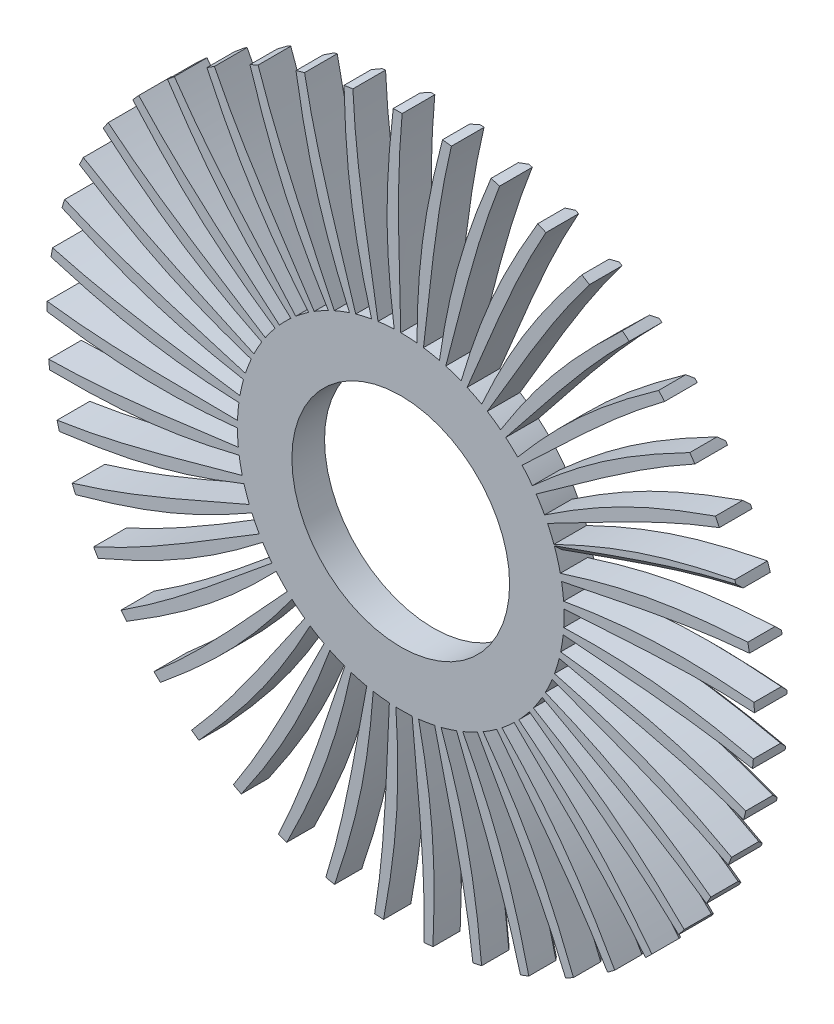
SolidWorks part; units mm, degrees
ref_plane "Front Plane" through (0, 0, 0) normal (0, 0, 1) x (1, 0, 0)
ref_plane "Top Plane" through (0, 0, 0) normal (0, 1, 0) x (1, 0, 0)
ref_plane "Right Plane" through (0, 0, 0) normal (1, 0, 0) x (0, 0, -1)
sketch "Sketch2" plane through (0, 0, 0) normal (0, 0, 1) x (1, 0, 0)
  arc A0 (255.3051, -201.1078) -> (260.3042, -194.5937) centre (0, 0) ccw
  arc A1 (-6, 149.88) -> (-20.876, 148.5402) centre (0, 0) ccw
  arc A2 (280.8092, -163.619) -> (284.8532, -156.4726) centre (0, 0) ccw
  arc A3 (315.0307, -79.8792) -> (316.9481, -71.8949) centre (0, 0) ccw
  arc A4 (323.0818, -35.258) -> (323.8695, -27.0846) centre (0, 0) ccw
  arc A5 (324.8446, 10.0494) -> (324.487, 18.2529) centre (0, 0) ccw
  arc A6 (300.8478, -122.9456) -> (303.8578, -115.3059) centre (0, 0) ccw
  arc A7 (224.8316, -234.6822) -> (230.6888, -228.9273) centre (0, 0) ccw
  arc A8 (66.3054, -318.1644) -> (74.3222, -316.3877) centre (0, 0) ccw
  arc A9 (109.9401, -305.8401) -> (117.6316, -302.965) centre (0, 0) ccw
  arc A10 (151.4349, -287.563) -> (158.6514, -283.6454) centre (0, 0) ccw
  arc A11 (21.3802, -324.296) -> (29.5663, -323.6523) centre (0, 0) ccw
  arc A12 (-23.9611, -324.1155) -> (-15.7652, -324.6174) centre (0, 0) ccw
  arc A13 (-68.8361, -317.6265) -> (-60.7898, -319.2642) centre (0, 0) ccw
  arc A14 (-112.3712, -304.9552) -> (-104.6312, -307.6968) centre (0, 0) ccw
  arc A15 (-153.7192, -286.3484) -> (-146.436, -290.1405) centre (0, 0) ccw
  arc A16 (-192.0752, -262.1681) -> (-185.3906, -266.9369) centre (0, 0) ccw
  arc A17 (-226.6927, -232.885) -> (-220.7369, -238.5377) centre (0, 0) ccw
  arc A18 (-256.8979, -199.069) -> (-251.7867, -205.4956) centre (0, 0) ccw
  arc A19 (-282.1028, -161.3784) -> (-277.9358, -168.4538) centre (0, 0) ccw
  arc A20 (-301.817, -120.5468) -> (-298.6752, -128.1333) centre (0, 0) ccw
  arc A21 (-315.6566, -77.3688) -> (-313.6012, -85.3187) centre (0, 0) ccw
  arc A22 (-323.3523, -32.685) -> (-322.4233, -40.8435) centre (0, 0) ccw
  arc A23 (-324.7543, 12.6351) -> (-324.9699, 4.4266) centre (0, 0) ccw
  arc A24 (-319.8354, 57.7092) -> (-321.1912, 49.6106) centre (0, 0) ccw
  arc A25 (-308.6912, 101.66) -> (-311.1609, 93.8289) centre (0, 0) ccw
  arc A26 (-291.5387, 143.6322) -> (-295.0743, 136.221) centre (0, 0) ccw
  arc A27 (-268.7117, 182.8087) -> (-273.2443, 175.9618) centre (0, 0) ccw
  arc A28 (-131.0066, 297.4261) -> (-138.4788, 294.0215) centre (0, 0) ccw
  arc A29 (-207.9134, 249.794) -> (-214.1577, 244.4616) centre (0, 0) ccw
  arc A30 (-171.1254, 276.2989) -> (-178.051, 271.8875) centre (0, 0) ccw
  arc A31 (-88.3379, 312.7641) -> (-96.2113, 310.4326) centre (0, 0) ccw
  arc A32 (-240.6546, 218.4271) -> (-246.096, 212.2776) centre (0, 0) ccw
  arc A33 (-43.9499, 322.0146) -> (-52.0711, 320.8015) centre (0, 0) ccw
  arc A34 (46.5119, 321.6545) -> (38.3709, 322.7269) centre (0, 0) ccw
  arc A35 (90.8249, 312.051) -> (82.9124, 314.246) centre (0, 0) ccw
  arc A36 (133.3701, 296.3738) -> (125.8401, 299.6486) centre (0, 0) ccw
  arc A37 (173.3194, 274.9279) -> (166.3185, 279.2189) centre (0, 0) ccw
  arc A38 (209.8953, 248.131) -> (203.5596, 253.3545) centre (0, 0) ccw
  arc A39 (242.3857, 216.5044) -> (236.8387, 222.5588) centre (0, 0) ccw
  arc A40 (270.1584, 180.6638) -> (265.508, 187.4313) centre (0, 0) ccw
  arc A41 (292.6728, 141.3068) -> (289.0095, 148.6557) centre (0, 0) ccw
  arc A42 (309.4907, 99.1994) -> (306.8858, 106.9866) centre (0, 0) ccw
  arc A43 (320.2846, 55.1613) -> (318.7888, 63.2352) centre (0, 0) ccw
  arc A44 (1.2936, 324.9974) -> (-6.9174, 324.9264) centre (0, 0) ccw
  arc A46 (-26.8009, 147.5863) -> (-41.3456, 144.1893) centre (0, 0) ccw
  arc A47 (-47.0801, 142.42) -> (-61.0105, 137.0318) centre (0, 0) ccw
  arc A48 (35.5449, 145.7277) -> (20.876, 148.5402) centre (0, 0) ccw
  arc A49 (14.9176, 149.2564) -> (0, 150) centre (0, 0) ccw
  arc A50 (-66.4429, 134.4817) -> (-79.4879, 127.2072) centre (0, 0) ccw
  arc A51 (-84.5126, 123.9259) -> (-96.4181, 114.9067) centre (0, 0) ccw
  arc A52 (-100.9372, 110.958) -> (-111.4717, 100.3696) centre (0, 0) ccw
  arc A53 (55.4804, 139.3626) -> (41.3456, 144.1893) centre (0, 0) ccw
  arc A54 (74.336, 130.2849) -> (61.0105, 137.0318) centre (0, 0) ccw
  arc A55 (91.7447, 118.6714) -> (79.4879, 127.2072) centre (0, 0) ccw
  arc A56 (-115.3973, 95.8304) -> (-124.3556, 83.8789) centre (0, 0) ccw
  arc A57 (-127.6113, 78.8376) -> (-134.8191, 65.7557) centre (0, 0) ccw
  arc A58 (107.3677, 104.7481) -> (96.4181, 114.9067) centre (0, 0) ccw
  arc A59 (120.901, 88.786) -> (111.4717, 100.3696) centre (0, 0) ccw
  arc A60 (132.081, 71.0958) -> (124.3556, 83.8789) centre (0, 0) ccw
  arc A61 (-137.3414, 60.3103) -> (-142.6585, 46.3525) centre (0, 0) ccw
  arc A62 (140.6902, 52.0218) -> (134.8191, 65.7557) centre (0, 0) ccw
  arc A63 (146.561, 31.9352) -> (142.6585, 46.3525) centre (0, 0) ccw
  arc A64 (-144.3984, 40.6091) -> (-147.7212, 26.0472) centre (0, 0) ccw
  arc A65 (-148.6448, 20.1175) -> (-149.9086, 5.2349) centre (0, 0) ccw
  arc A66 (-149.998, -0.7656) -> (-149.1783, -15.6793) centre (0, 0) ccw
  arc A67 (-148.4317, -21.6339) -> (-145.5444, -36.2883) centre (0, 0) ccw
  arc A68 (-143.9763, -42.081) -> (-139.0776, -56.191) centre (0, 0) ccw
  arc A69 (-136.7186, -61.7091) -> (-129.9038, -75) centre (0, 0) ccw
  arc A70 (-126.7998, -80.1361) -> (-118.2016, -92.3492) centre (0, 0) ccw
  arc A71 (-114.413, -97.0034) -> (-104.1988, -107.901) centre (0, 0) ccw
  arc A72 (-99.7993, -111.9826) -> (-88.1678, -121.3525) centre (0, 0) ccw
  arc A73 (-83.2431, -124.7821) -> (-70.4207, -132.4421) centre (0, 0) ccw
  arc A74 (-65.0667, -135.153) -> (-51.303, -140.9539) centre (0, 0) ccw
  arc A75 (-45.6238, -142.8932) -> (-31.1868, -146.7221) centre (0, 0) ccw
  arc A76 (-25.2929, -147.8522) -> (-10.4635, -149.6346) centre (0, 0) ccw
  arc A77 (-4.4697, -149.9334) -> (10.4635, -149.6346) centre (0, 0) ccw
  arc A78 (16.4405, -149.0963) -> (31.1868, -146.7221) centre (0, 0) ccw
  arc A79 (37.0307, -145.3572) -> (51.303, -140.9539) centre (0, 0) ccw
  arc A80 (56.9001, -138.789) -> (70.4207, -132.4421) centre (0, 0) ccw
  arc A81 (75.6621, -129.5193) -> (88.1678, -121.3525) centre (0, 0) ccw
  arc A82 (108.4314, -103.6467) -> (118.2016, -92.3492) centre (0, 0) ccw
  arc A83 (121.801, -87.5472) -> (129.9038, -75) centre (0, 0) ccw
  arc A84 (132.7998, -69.7438) -> (139.0776, -56.191) centre (0, 0) ccw
  arc A85 (141.2139, -50.5829) -> (145.5444, -36.2883) centre (0, 0) ccw
  arc A86 (146.8794, -30.4375) -> (149.1783, -15.6793) centre (0, 0) ccw
  arc A87 (92.9513, -117.7287) -> (104.1988, -107.901) centre (0, 0) ccw
  arc A88 (149.6861, -9.6996) -> (149.9086, 5.2349) centre (0, 0) ccw
  arc A89 (149.5793, 11.2271) -> (147.7212, 26.0472) centre (0, 0) ccw
  arc A90 (189.9822, -263.6888) -> (196.5832, -258.805) centre (0, 0) ccw
  spline S0 degree 3 poles (-6, 149.88) (-14.2223, 209.3858) (-13.9707, 256.8737) (-8.1395, 314.3894) (-7.1988, 322.5645) (-6.9174, 324.9264) knots 0 0 0 0 0.599001 0.668692 0.696915 0.696915 0.696915 0.696915
  spline S1 degree 3 poles (0, 150) (-1.2357, 209.7616) (-4.4377, 264.7336) (1.2936, 324.9974) knots 0 0 0 0 0.71612 0.71612 0.71612 0.71612
  spline S2 degree 3 poles (14.9176, 149.2564) (15.0569, 209.3274) (21.9152, 256.3182) (35.6943, 312.4626) (37.7635, 320.4272) (38.3709, 322.7269) knots 0 0 0 0 0.599001 0.668692 0.696915 0.696915 0.696915 0.696915
  spline S3 degree 3 poles (20.876, 148.5402) (27.9695, 207.8922) (32.4492, 262.7748) (46.5119, 321.6545) knots 0 0 0 0 0.71612 0.71612 0.71612 0.71612
  spline S4 degree 3 poles (35.5449, 145.7277) (44.0431, 205.1947) (57.3745, 250.7737) (78.8333, 304.4541) (81.9909, 312.0532) (82.9124, 314.246) knots 0 0 0 0 0.599001 0.668692 0.696915 0.696915 0.696915 0.696915
  spline S5 degree 3 poles (41.3456, 144.1893) (56.6303, 201.9765) (68.7046, 255.7014) (90.8249, 312.051) knots 0 0 0 0 0.71612 0.71612 0.71612 0.71612
  spline S6 degree 3 poles (55.4804, 139.3626) (72.1721, 197.0682) (91.7171, 240.3482) (120.4379, 290.5197) (124.6224, 297.6054) (125.8401, 299.6486) knots 0 0 0 0 0.599001 0.668692 0.696915 0.696915 0.696915 0.696915
  spline S7 degree 3 poles (61.0105, 137.0318) (84.1888, 192.1294) (103.6228, 243.6511) (133.3701, 296.3738) knots 0 0 0 0 0.71612 0.71612 0.71612 0.71612
  spline S8 degree 3 poles (74.336, 130.2849) (98.8963, 185.1059) (124.2745, 225.2446) (159.6984, 270.9306) (164.8282, 277.365) (166.3185, 279.2189) knots 0 0 0 0 0.599001 0.668692 0.696915 0.696915 0.696915 0.696915
  spline S9 degree 3 poles (79.4879, 127.2072) (110.1088, 178.5428) (136.524, 226.8584) (173.3194, 274.9279) knots 0 0 0 0 0.71612 0.71612 0.71612 0.71612
  spline S10 degree 3 poles (91.7447, 118.6714) (123.6956, 169.5408) (154.413, 205.7569) (195.8505, 246.0682) (201.8259, 251.7261) (203.5596, 253.3545) knots 0 0 0 0 0.599001 0.668692 0.696915 0.696915 0.696915 0.696915
  spline S11 degree 3 poles (96.4181, 114.9067) (133.8856, 161.4811) (166.768, 205.6502) (209.8953, 248.131) knots 0 0 0 0 0.71612 0.71612 0.71612 0.71612
  spline S12 degree 3 poles (107.3677, 104.7481) (146.0874, 150.6757) (181.5461, 182.2643) (228.1905, 216.4164) (234.8952, 221.1876) (236.8387, 222.5588) knots 0 0 0 0 0.599001 0.668692 0.696915 0.696915 0.696915 0.696915
  spline S13 degree 3 poles (111.4717, 100.3696) (155.0564, 141.2763) (193.766, 180.4392) (242.3857, 216.5044) knots 0 0 0 0 0.71612 0.71612 0.71612 0.71612
  spline S14 degree 3 poles (120.901, 88.786) (165.6356, 128.8779) (205.1456, 155.2242) (256.0891, 182.5523) (263.3926, 186.3439) (265.508, 187.4313) knots 0 0 0 0 0.599001 0.668692 0.696915 0.696915 0.696915 0.696915
  spline S15 degree 3 poles (124.3556, 83.8789) (173.2093, 118.3217) (216.9925, 151.7162) (270.1584, 180.6638) knots 0 0 0 0 0.71612 0.71612 0.71612 0.71612
  spline S16 degree 3 poles (132.081, 71.0958) (181.96, 104.5716) (224.7522, 125.1628) (279.0033, 145.135) (286.7633, 147.8732) (289.0095, 148.6557) knots 0 0 0 0 0.599001 0.668692 0.696915 0.696915 0.696915 0.696915
  spline S17 degree 3 poles (134.8191, 65.7557) (187.9908, 93.0641) (235.9956, 120.0402) (292.6728, 141.3068) knots 0 0 0 0 0.71612 0.71612 0.71612 0.71612
  spline S18 degree 3 poles (140.6902, 52.0218) (194.7428, 78.23) (239.9842, 92.6653) (296.4869, 104.8928) (304.5525, 106.5244) (306.8858, 106.9866) knots 0 0 0 0 0.599001 0.668692 0.696915 0.696915 0.696915 0.696915
  spline S19 degree 3 poles (142.6585, 46.3525) (199.1133, 65.9952) (250.4052, 86.0277) (309.4907, 99.1994) knots 0 0 0 0 0.71612 0.71612 0.71612 0.71612
  spline S20 degree 3 poles (146.561, 31.9352) (203.7351, 50.3657) (250.5452, 58.3641) (308.1998, 62.609) (316.414, 63.1022) (318.7888, 63.2352) knots 0 0 0 0 0.599001 0.668692 0.696915 0.696915 0.696915 0.696915
  spline S21 degree 3 poles (147.7212, 26.0472) (206.3603, 37.6417) (259.9411, 50.3408) (320.2846, 55.1613) knots 0 0 0 0 0.71612 0.71612 0.71612 0.71612
  spline S22 degree 3 poles (149.5793, 11.2271) (208.7619, 21.5211) (256.2296, 22.927) (313.9139, 19.1065) (322.1168, 18.4518) (324.487, 18.2529) knots 0 0 0 0 0.599001 0.668692 0.696915 0.696915 0.696915 0.696915
  spline S23 degree 3 poles (149.9086, 5.2349) (209.5907, 8.5556) (264.4174, 13.6741) (324.8446, 10.0494) knots 0 0 0 0 0.71612 0.71612 0.71612 0.71612
  spline S24 degree 3 poles (149.6861, -9.6996) (209.7254, -7.7423) (256.9268, -12.9564) (313.518, -24.7678) (321.55, -26.5578) (323.8695, -27.0846) knots 0 0 0 0 0.599001 0.668692 0.696915 0.696915 0.696915 0.696915
  spline S25 degree 3 poles (149.1783, -15.6793) (208.7417, -20.6971) (263.7472, -23.2588) (323.0818, -35.258) knots 0 0 0 0 0.71612 0.71612 0.71612 0.71612
  spline S26 degree 3 poles (146.8794, -30.4375) (206.6068, -36.8551) (252.6233, -48.5876) (307.0199, -68.16) (314.7245, -71.0504) (316.9481, -71.8949) knots 0 0 0 0 0.599001 0.668692 0.696915 0.696915 0.696915 0.696915
  spline S27 degree 3 poles (145.5444, -36.2883) (203.8298, -49.5469) (257.9434, -59.7389) (315.0307, -79.8792) knots 0 0 0 0 0.71612 0.71612 0.71612 0.71612
  spline S28 degree 3 poles (141.2139, -50.5829) (199.4669, -65.2506) (243.4027, -83.2732) (294.5459, -110.2256) (301.7734, -114.1602) (303.8578, -115.3059) knots 0 0 0 0 0.599001 0.668692 0.696915 0.696915 0.696915 0.696915
  spline S29 degree 3 poles (139.0776, -56.191) (194.9505, -77.4323) (247.1191, -95.0563) (300.8478, -122.9456) knots 0 0 0 0 0.71612 0.71612 0.71612 0.71612
  spline S30 degree 3 poles (132.7998, -69.7438) (188.4446, -92.376) (229.4445, -116.3378) (276.339, -150.1457) (282.9485, -155.0479) (284.8532, -156.4726) knots 0 0 0 0 0.599001 0.668692 0.696915 0.696915 0.696915 0.696915
  spline S31 degree 3 poles (129.9038, -75) (182.2768, -103.8106) (231.4849, -128.5236) (280.8092, -163.619) knots 0 0 0 0 0.71612 0.71612 0.71612 0.71612
  spline S32 degree 3 poles (121.801, -87.5472) (173.7544, -117.7034) (211.0205, -147.1382) (252.7534, -187.1435) (258.6164, -192.9178) (260.3042, -194.5937) knots 0 0 0 0 0.599001 0.668692 0.696915 0.696915 0.696915 0.696915
  spline S33 degree 3 poles (118.2016, -92.3492) (166.0552, -128.1684) (211.345, -159.4893) (255.3051, -201.1078) knots 0 0 0 0 0.71612 0.71612 0.71612 0.71612
  spline S34 degree 3 poles (108.4314, -103.6467) (155.6823, -140.7399) (188.4891, -175.0746) (224.2483, -220.4987) (229.2506, -227.0328) (230.6888, -228.9273) knots 0 0 0 0 0.599001 0.668692 0.696915 0.696915 0.696915 0.696915
  spline S35 degree 3 poles (104.1988, -107.901) (146.6016, -150.0315) (187.0916, -187.3507) (224.8316, -234.6822) knots 0 0 0 0 0.71612 0.71612 0.71612 0.71612
  spline S36 degree 3 poles (92.9513, -117.7287) (134.58, -161.037) (162.2891, -199.6034) (191.3784, -249.5622) (195.4226, -256.7288) (196.5832, -258.805) knots 0 0 0 0 0.599001 0.668692 0.696915 0.696915 0.696915 0.696915
  spline S37 degree 3 poles (88.1678, -121.3525) (124.2945, -168.9744) (159.1967, -211.5655) (189.9822, -263.6888) knots 0 0 0 0 0.71612 0.71612 0.71612 0.71612
  spline S38 degree 3 poles (75.6621, -129.5193) (110.8583, -178.1997) (132.9303, -220.2471) (154.7836, -273.7682) (157.7911, -281.4279) (158.6514, -283.6454) knots 0 0 0 0 0.599001 0.668692 0.696915 0.696915 0.696915 0.696915
  spline S39 degree 3 poles (70.4207, -132.4421) (99.5682, -184.6284) (128.2032, -231.6625) (151.4349, -287.563) knots 0 0 0 0 0.71612 0.71612 0.71612 0.71612
  spline S40 degree 3 poles (56.9001, -138.789) (84.9788, -191.8939) (100.9842, -236.604) (115.1761, -292.6456) (117.0882, -300.6494) (117.6316, -302.965) knots 0 0 0 0 0.599001 0.668692 0.696915 0.696915 0.696915 0.696915
  spline S41 degree 3 poles (51.303, -140.9539) (72.9039, -196.6888) (94.7143, -247.2504) (109.9401, -305.8401) knots 0 0 0 0 0.71612 0.71612 0.71612 0.71612
  spline S42 degree 3 poles (37.0307, -145.3572) (57.4453, -201.8532) (67.0725, -248.3557) (73.3268, -305.827) (74.1064, -314.019) (74.3222, -316.3877) knots 0 0 0 0 0.599001 0.668692 0.696915 0.696915 0.696915 0.696915
  spline S43 degree 3 poles (31.1868, -146.7221) (44.8206, -204.9209) (59.382, -258.0258) (66.3054, -318.1644) knots 0 0 0 0 0.71612 0.71612 0.71612 0.71612
  spline S44 degree 3 poles (16.4405, -149.0963) (28.7937, -207.8836) (31.8553, -255.2734) (30.0503, -313.0558) (29.6823, -321.2766) (29.5663, -323.6523) knots 0 0 0 0 0.599001 0.668692 0.696915 0.696915 0.696915 0.696915
  spline S45 degree 3 poles (10.4635, -149.6346) (15.865, -209.1645) (22.8938, -263.7791) (21.3802, -324.296) knots 0 0 0 0 0.71612 0.71612 0.71612 0.71612
  spline S46 degree 3 poles (-4.4697, -149.9334) (-0.4183, -209.8678) (-3.9819, -257.2225) (-13.8111, -314.1914) (-15.3197, -322.2809) (-15.7652, -324.6174) knots 0 0 0 0 0.599001 0.668692 0.696915 0.696915 0.696915 0.696915
  spline S47 degree 3 poles (-10.4635, -149.6346) (-13.3995, -209.3369) (-14.04, -264.3982) (-23.9611, -324.1155) knots 0 0 0 0 0.71612 0.71612 0.71612 0.71612
  spline S48 degree 3 poles (-25.2929, -147.8522) (-29.6222, -207.7672) (-39.7416, -254.1651) (-57.4037, -309.2116) (-60.0234, -317.0124) (-60.7898, -319.2642) knots 0 0 0 0 0.599001 0.668692 0.696915 0.696915 0.696915 0.696915
  spline S49 degree 3 poles (-31.1868, -146.7221) (-42.4032, -205.4348) (-50.7004, -259.8712) (-68.8361, -317.6265) knots 0 0 0 0 0.71612 0.71612 0.71612 0.71612
  spline S50 degree 3 poles (-45.6238, -142.8932) (-58.2495, -201.6226) (-74.7278, -246.1606) (-99.8789, -298.2133) (-103.5589, -305.5737) (-104.6312, -307.6968) knots 0 0 0 0 0.599001 0.668692 0.696915 0.696915 0.696915 0.696915
  spline S51 degree 3 poles (-51.303, -140.9539) (-70.5815, -197.5341) (-86.3741, -250.286) (-112.3712, -304.9552) knots 0 0 0 0 0.71612 0.71612 0.71612 0.71612
  spline S52 degree 3 poles (-65.0667, -135.153) (-85.7431, -191.5537) (-108.2595, -233.3649) (-140.4102, -281.4106) (-145.0787, -288.1872) (-146.436, -290.1405) knots 0 0 0 0 0.599001 0.668692 0.696915 0.696915 0.696915 0.696915
  spline S53 degree 3 poles (-70.4207, -132.4421) (-97.386, -185.7887) (-120.3666, -235.8293) (-153.7192, -286.3484) knots 0 0 0 0 0.71612 0.71612 0.71612 0.71612
  spline S54 degree 3 poles (-83.2431, -124.7821) (-111.5678, -177.7563) (-139.684, -216.027) (-178.2085, -259.1307) (-183.7747, -265.1915) (-185.3906, -266.9369) knots 0 0 0 0 0.599001 0.668692 0.696915 0.696915 0.696915 0.696915
  spline S55 degree 3 poles (-88.1678, -121.3525) (-122.2951, -170.4271) (-152.0163, -216.7824) (-192.0752, -262.1681) knots 0 0 0 0 0.71612 0.71612 0.71612 0.71612
  spline S56 degree 3 poles (-99.7993, -111.9826) (-135.2209, -160.4992) (-168.3898, -194.4843) (-212.5382, -231.807) (-218.8937, -237.0342) (-220.7369, -238.5377) knots 0 0 0 0 0.599001 0.668692 0.696915 0.696915 0.696915 0.696915
  spline S57 degree 3 poles (-104.1988, -107.901) (-144.8238, -151.7483) (-180.7071, -193.5161) (-226.6927, -232.885) knots 0 0 0 0 0.71612 0.71612 0.71612 0.71612
  spline S58 degree 3 poles (-114.413, -97.0034) (-156.2421, -140.1181) (-193.818, -169.1563) (-242.7311, -199.9715) (-249.7523, -204.2633) (-251.7867, -205.4956) knots 0 0 0 0 0.599001 0.668692 0.696915 0.696915 0.696915 0.696915
  spline S59 degree 3 poles (-118.2016, -92.3492) (-164.5336, -130.1159) (-205.8808, -166.4832) (-256.8979, -199.069) knots 0 0 0 0 0.71612 0.71612 0.71612 0.71612
  spline S60 degree 3 poles (-126.7998, -80.1361) (-174.2222, -117.0098) (-215.4738, -140.5358) (-268.1995, -164.2437) (-275.7497, -167.5166) (-277.9358, -168.4538) knots 0 0 0 0 0.599001 0.668692 0.696915 0.696915 0.696915 0.696915
  spline S61 degree 3 poles (-129.9038, -75) (-181.041, -105.951) (-227.0471, -136.21) (-282.1028, -161.3784) knots 0 0 0 0 0.71612 0.71612 0.71612 0.71612
  spline S62 degree 3 poles (-136.7186, -61.7091) (-188.8113, -91.624) (-232.9356, -109.18) (-288.4477, -125.3191) (-296.3799, -127.5094) (-298.6752, -128.1333) knots 0 0 0 0 0.599001 0.668692 0.696915 0.696915 0.696915 0.696915
  spline S63 degree 3 poles (-139.0776, -56.191) (-194.0247, -79.7239) (-243.7943, -103.2855) (-301.817, -120.5468) knots 0 0 0 0 0.71612 0.71612 0.71612 0.71612
  spline S64 degree 3 poles (-143.9763, -42.081) (-199.7254, -64.4549) (-245.8636, -75.6991) (-303.0816, -83.9554) (-311.2414, -85.0204) (-313.6012, -85.3187) knots 0 0 0 0 0.599001 0.668692 0.696915 0.696915 0.696915 0.696915
  spline S65 degree 3 poles (-145.5444, -36.2883) (-203.2319, -51.945) (-255.7963, -68.3508) (-315.6566, -77.3688) knots 0 0 0 0 0.71612 0.71612 0.71612 0.71612
  spline S66 degree 3 poles (-148.4317, -21.6339) (-206.7521, -36.0312) (-254.0062, -40.7448) (-311.8164, -40.9575) (-320.045, -40.8766) (-322.4233, -40.8435) knots 0 0 0 0 0.599001 0.668692 0.696915 0.696915 0.696915 0.696915
  spline S67 degree 3 poles (-149.1783, -15.6793) (-208.4834, -23.155) (-262.8195, -32.0856) (-323.3523, -32.685) knots 0 0 0 0 0.71612 0.71612 0.71612 0.71612
  spline S68 degree 3 poles (-149.998, -0.7656) (-209.7546, -6.9062) (-257.2048, -4.9974) (-314.482, 2.8375) (-322.6193, 4.0629) (-324.9699, 4.4266) knots 0 0 0 0 0.599001 0.668692 0.696915 0.696915 0.696915 0.696915
  spline S69 degree 3 poles (-149.9086, 5.2349) (-209.677, 6.0856) (-264.7272, 4.804) (-324.7543, 12.6351) knots 0 0 0 0 0.71612 0.71612 0.71612 0.71612
  spline S70 degree 3 poles (-148.6448, 20.1175) (-208.6744, 22.3532) (-255.3972, 30.8472) (-311.0266, 46.5774) (-318.9141, 48.9233) (-321.1912, 49.6106) knots 0 0 0 0 0.599001 0.668692 0.696915 0.696915 0.696915 0.696915
  spline S71 degree 3 poles (-147.7212, 26.0472) (-206.7895, 35.2078) (-261.4823, 41.6002) (-319.8354, 57.7092) knots 0 0 0 0 0.71612 0.71612 0.71612 0.71612
  spline S72 degree 3 poles (-144.3984, 40.6091) (-203.5327, 51.1775) (-248.6186, 66.0914) (-301.5174, 89.4106) (-309.0017, 92.8314) (-311.1609, 93.8289) knots 0 0 0 0 0.599001 0.668692 0.696915 0.696915 0.696915 0.696915
  spline S73 degree 3 poles (-142.6585, 46.3525) (-199.877, 63.6447) (-253.1479, 77.5866) (-308.6912, 101.66) knots 0 0 0 0 0.71612 0.71612 0.71612 0.71612
  spline S74 degree 3 poles (-137.3414, 60.3103) (-194.4294, 79.0057) (-237.0009, 100.0492) (-286.1395, 130.5036) (-293.0748, 134.9327) (-295.0743, 136.221) knots 0 0 0 0 0.599001 0.668692 0.696915 0.696915 0.696915 0.696915
  spline S75 degree 3 poles (-134.8191, 65.7557) (-189.0742, 90.8428) (-239.8863, 112.0629) (-291.5387, 143.6322) knots 0 0 0 0 0.71612 0.71612 0.71612 0.71612
  spline S76 degree 3 poles (-127.6113, 78.8376) (-181.5417, 105.2962) (-220.7703, 132.0597) (-265.1922, 169.0564) (-271.4436, 174.4077) (-273.2443, 175.9618) knots 0 0 0 0 0.599001 0.668692 0.696915 0.696915 0.696915 0.696915
  spline S77 degree 3 poles (-124.3556, 83.8789) (-174.5913, 116.2728) (-221.9556, 144.3581) (-268.7117, 182.8087) knots 0 0 0 0 0.71612 0.71612 0.71612 0.71612
  spline S78 degree 3 poles (-115.3973, 95.8304) (-165.1206, 129.5372) (-200.2426, 161.4998) (-239.0833, 204.3188) (-244.5291, 210.488) (-246.096, 212.2776) knots 0 0 0 0 0.599001 0.668692 0.696915 0.696915 0.696915 0.696915
  spline S79 degree 3 poles (-111.4717, 100.3696) (-156.7102, 139.4396) (-199.7048, 173.8434) (-240.6546, 218.4271) knots 0 0 0 0 0.71612 0.71612 0.71612 0.71612
  spline S80 degree 3 poles (-100.9372, 110.958) (-145.4855, 151.2569) (-175.8174, 187.7965) (-208.3208, 235.6043) (-212.8551, 242.4715) (-214.1577, 244.4616) knots 0 0 0 0 0.599001 0.668692 0.696915 0.696915 0.696915 0.696915
  spline S81 degree 3 poles (-96.4181, 114.9067) (-135.7788, 159.8924) (-173.567, 199.9452) (-207.9134, 249.794) knots 0 0 0 0 0.71612 0.71612 0.71612 0.71612
  spline S82 degree 3 poles (-84.5126, 123.9259) (-123.0188, 170.0325) (-147.9702, 210.4379) (-173.5037, 262.3041) (-177.0381, 269.7354) (-178.051, 271.8875) knots 0 0 0 0 0.599001 0.668692 0.696915 0.696915 0.696915 0.696915
  spline S83 degree 3 poles (-79.4879, 127.2072) (-112.2047, 177.2331) (-144.0508, 222.1552) (-171.1254, 276.2989) knots 0 0 0 0 0.71612 0.71612 0.71612 0.71612
  spline S84 degree 3 poles (-66.4429, 134.4817) (-98.1576, 185.4987) (-117.2428, 228.9834) (-135.3095, 283.8984) (-137.7753, 291.7493) (-138.4788, 294.0215) knots 0 0 0 0 0.599001 0.668692 0.696915 0.696915 0.696915 0.696915
  spline S85 degree 3 poles (-61.0105, 137.0318) (-86.4466, 191.1242) (-111.7309, 240.0412) (-131.0066, 297.4261) knots 0 0 0 0 0.71612 0.71612 0.71612 0.71612
  spline S86 degree 3 poles (-47.0801, 142.42) (-71.3859, 197.3543) (-84.2335, 243.072) (-94.4816, 299.967) (-95.8308, 308.0847) (-96.2113, 310.4326) knots 0 0 0 0 0.599001 0.668692 0.696915 0.696915 0.696915 0.696915
  spline S87 degree 3 poles (-41.3456, 144.1893) (-59.006, 201.2952) (-77.2363, 253.255) (-88.3379, 312.7641) knots 0 0 0 0 0.71612 0.71612 0.71612 0.71612
  spline S88 degree 3 poles (-26.8009, 147.5863) (-43.2248, 205.3687) (-49.5847, 252.4295) (-51.8148, 310.197) (-52.0211, 318.4235) (-52.0711, 320.8015) knots 0 0 0 0 0.599001 0.668692 0.696915 0.696915 0.696915 0.696915
  spline S89 degree 3 poles (-20.876, 148.5402) (-30.4169, 207.5483) (-41.2383, 261.5396) (-43.9499, 322.0146) knots 0 0 0 0 0.71612 0.71612 0.71612 0.71612
  point P230 (0, 0)
  dimension "D2" = 300
  dimension "D3" = 45
extrude "Boss-Extrude1" add sketch "Sketch2" along normal blind 30
chamfer "Chamfer1" distance 5 angle 45 45 edges
sketch "Sketch4" plane through (0, 0, 30) normal (0, 0, 1) x (1, 0, 0)
  circle A0 centre (0, 0) radius 100
  dimension "D1" = 200
extrude "Cut-Extrude4" cut sketch "Sketch4" against normal blind 30
